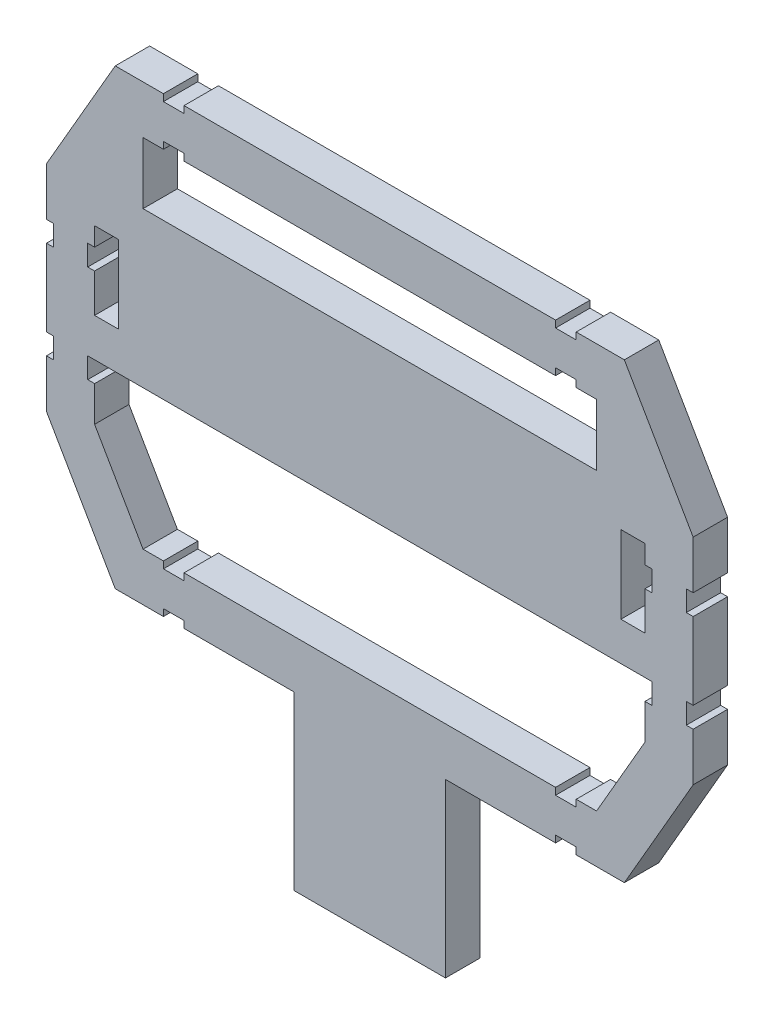
SolidWorks part; units mm, degrees
ref_plane "Plan de face" through (0, 0, 0) normal (0, 0, 1) x (1, 0, 0)
ref_plane "Plan de dessus" through (0, 0, 0) normal (0, 1, 0) x (1, 0, 0)
ref_plane "Plan de droite" through (0, 0, 0) normal (1, 0, 0) x (0, 0, -1)
sketch "Esquisse1" plane through (0, 0, 0) normal (0, 0, 1) x (1, 0, 0)
  line L0 (-16, -30.0222) -> (-16, -55.0222) construction
  line L1 (-32, -30.0222) -> (-32, -29.0222)
  line L2 (-32, -29.0222) -> (-35, -29.0222)
  line L3 (-35, -29.0222) -> (-35, -30.0222)
  line L4 (-35, -30.0222) -> (-42, -30.0222)
  line L5 (-42, -30.0222) -> (-52, -12.7017)
  line L6 (-52, -12.7017) -> (-52, -5.7017)
  line L7 (-52, -5.7017) -> (-51, -5.7017)
  line L8 (-51, -5.7017) -> (-51, -2.7017)
  line L9 (-51, -2.7017) -> (-52, -2.7017)
  line L10 (-52, -2.7017) -> (-52, 8.4752)
  line L11 (-5, -30.0222) -> (-5, 35.7957) construction
  line L12 (35, 2.8868) -> (-45, 2.8868) construction
  line L13 (-47, -21.362) -> (-5, 2.8868) construction
  line L14 (-45, 8.4752) -> (-45, -2.7017)
  line L15 (-45, -2.7017) -> (-46, -2.7017)
  line L16 (-46, -2.7017) -> (-46, -5.7017)
  line L17 (-46, -5.7017) -> (-45, -5.7017)
  line L18 (-45, -5.7017) -> (-45, -10.8261)
  line L19 (-45, -10.8261) -> (-37.9585, -23.0222)
  line L20 (-37.9585, -23.0222) -> (-35, -23.0222)
  line L21 (-35, -23.0222) -> (-35, -24.0222)
  line L22 (-35, -24.0222) -> (-32, -24.0222)
  line L23 (-32, -24.0222) -> (-32, -23.0222)
  line L24 (-32, -23.0222) -> (22, -23.0222)
  line L25 (-47, 27.1355) -> (-5, 2.8868) construction
  line L26 (-32, 28.7957) -> (22, 28.7957)
  line L27 (-32, 29.7957) -> (-32, 28.7957)
  line L28 (-35, 29.7957) -> (-32, 29.7957)
  line L29 (-35, 28.7957) -> (-35, 29.7957)
  line L30 (-37.9585, 28.7957) -> (-35, 28.7957)
  line L31 (-37.9585, 28.7957) -> (-37.9585, 19.8426)
  line L32 (-37.9585, 19.8426) -> (27.9585, 19.8426)
  line L33 (-46, 11.4752) -> (-45, 11.4752)
  line L34 (-46, 8.4752) -> (-46, 11.4752)
  line L35 (-45, 8.4752) -> (-46, 8.4752)
  line L36 (-51, 8.4752) -> (-52, 8.4752)
  line L37 (-51, 11.4752) -> (-51, 8.4752)
  line L38 (-52, 11.4752) -> (-51, 11.4752)
  line L39 (-52, 18.4752) -> (-52, 11.4752)
  line L40 (-42, 35.7957) -> (-52, 18.4752)
  line L41 (-35, 35.7957) -> (-42, 35.7957)
  line L42 (-35, 34.7957) -> (-35, 35.7957)
  line L43 (-32, 34.7957) -> (-35, 34.7957)
  line L44 (-32, 35.7957) -> (-32, 34.7957)
  line L45 (22, 35.7957) -> (-32, 35.7957)
  line L46 (37, 27.1355) -> (-5, 2.8868) construction
  line L47 (37, -21.362) -> (-5, 2.8868) construction
  line L48 (22, 35.7957) -> (22, 34.7957)
  line L49 (22, 34.7957) -> (25, 34.7957)
  line L50 (25, 34.7957) -> (25, 35.7957)
  line L51 (25, 35.7957) -> (32, 35.7957)
  line L52 (32, 35.7957) -> (42, 18.4752)
  line L53 (42, 18.4752) -> (42, 11.4752)
  line L54 (42, 11.4752) -> (41, 11.4752)
  line L55 (41, 11.4752) -> (41, 8.4752)
  line L56 (41, 8.4752) -> (42, 8.4752)
  line L57 (35, 8.4752) -> (36, 8.4752)
  line L58 (36, 8.4752) -> (36, 11.4752)
  line L59 (36, 11.4752) -> (35, 11.4752)
  line L60 (27.9585, 19.8426) -> (27.9585, 28.7957)
  line L61 (35, -2.7017) -> (-45, -2.7017)
  line L62 (27.9585, 28.7957) -> (25, 28.7957)
  line L63 (25, 28.7957) -> (25, 29.7957)
  line L64 (25, 29.7957) -> (22, 29.7957)
  line L65 (22, 29.7957) -> (22, 28.7957)
  line L66 (22, -24.0222) -> (22, -23.0222)
  line L67 (25, -24.0222) -> (22, -24.0222)
  line L68 (25, -23.0222) -> (25, -24.0222)
  line L69 (27.9585, -23.0222) -> (25, -23.0222)
  line L70 (35, -10.8261) -> (27.9585, -23.0222)
  line L71 (35, -5.7017) -> (35, -10.8261)
  line L72 (36, -5.7017) -> (35, -5.7017)
  line L73 (36, -2.7017) -> (36, -5.7017)
  line L74 (35, -2.7017) -> (36, -2.7017)
  line L75 (35, 8.4752) -> (35, -2.7017)
  line L76 (42, -2.7017) -> (42, 8.4752)
  line L77 (41, -2.7017) -> (42, -2.7017)
  line L78 (41, -5.7017) -> (41, -2.7017)
  line L79 (42, -5.7017) -> (41, -5.7017)
  line L80 (42, -12.7017) -> (42, -5.7017)
  line L81 (32, -30.0222) -> (42, -12.7017)
  line L82 (25, -30.0222) -> (32, -30.0222)
  line L83 (25, -29.0222) -> (25, -30.0222)
  line L84 (22, -29.0222) -> (25, -29.0222)
  line L85 (22, -30.0222) -> (22, -29.0222)
  line L86 (35, 2.8868) -> (31.5, 2.8868)
  line L87 (31.5, 2.8868) -> (31.5, 14.1772)
  line L88 (31.5, 14.1772) -> (35, 14.1772)
  line L89 (35, 14.1772) -> (35, 11.4752)
  line L90 (35, 11.4752) -> (34.9646, 11.6959)
  line L91 (-45, 2.8868) -> (-41.5, 2.8868)
  line L92 (-41.5, 2.8868) -> (-41.5, 14.1772)
  line L93 (-41.5, 14.1772) -> (-45, 14.1772)
  line L94 (-45, 14.1772) -> (-45, 11.4752)
  line L95 (-16, -30.0222) -> (-16, -55.0222)
  line L96 (-16, -55.0222) -> (6, -55.0222)
  line L97 (6, -55.0222) -> (6, -30.0222)
  line L98 (6, -30.0222) -> (22, -30.0222)
  line L99 (-16, -30.0222) -> (-32, -30.0222)
  line L100 (6, -55.0222) -> (6, -30.0222) construction
  line L101 (-16, -55.0222) -> (6, -55.0222) construction
  point P10 (-47, -21.362)
  point P41 (-52, 2.8868)
  point P73 (-5, 28.7957)
  point P74 (-5, -23.0222)
  point P75 (-5, -23.0222)
  point P94 (42, 2.8868)
  dimension "D1" = 1
  dimension "D2" = 3
  dimension "D3" = 7
  dimension "D4" = 3
  dimension "D5" = 7
  dimension "D6" = 60
  dimension "D7" = 90
  dimension "D8" = 1
  dimension "D9" = 1
  dimension "D10" = 1
  dimension "D11" = 7
  dimension "D13" = 7
  dimension "D14" = 20
  dimension "D15" = 30
  dimension "D16" = 2.702
  dimension "D17" = 3.5
extrude "Boss.-Extru.1" add sketch "Esquisse1" along normal blind 5
